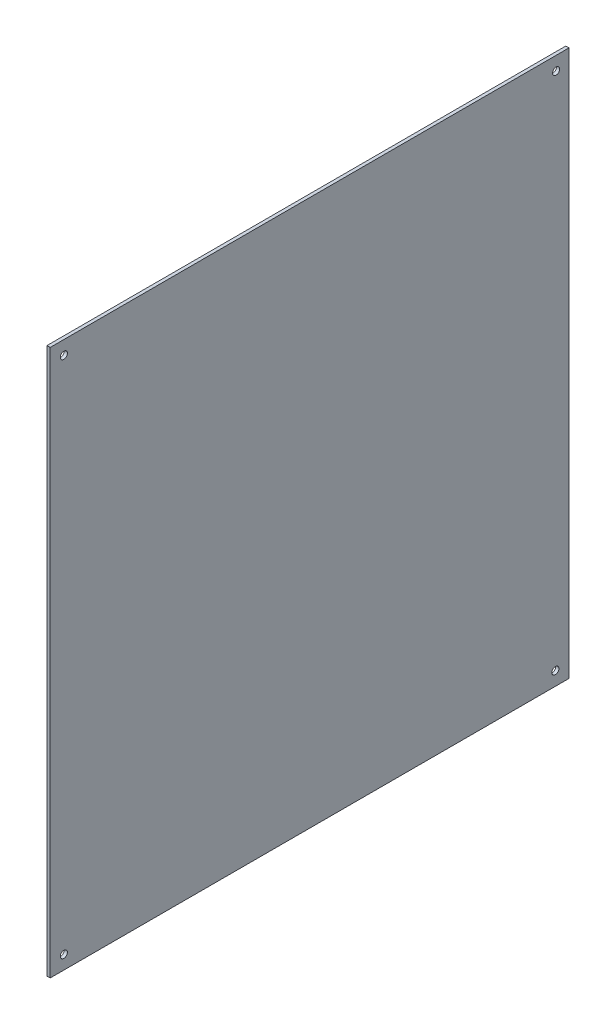
SolidWorks part; units mm, degrees
ref_plane "Front Plane" through (0, 0, 0) normal (0, 0, 1) x (1, 0, 0)
ref_plane "Top Plane" through (0, 0, 0) normal (0, 1, 0) x (1, 0, 0)
ref_plane "Right Plane" through (0, 0, 0) normal (1, 0, 0) x (0, 0, -1)
sketch "Sketch1" plane through (0, 0, 0) normal (1, 0, 0) x (0, 0, -1)
  line L1 (521.5242, 0) -> (1004.1242, 0)
  line L2 (521.5242, 0) -> (521.5242, -508)
  line L3 (521.5242, -508) -> (1004.1242, -508)
  line L4 (1004.1242, 0) -> (1004.1242, -508)
  dimension "D1" = 482.6
  dimension "D2" = 508
extrude "Boss-Extrude1" add sketch "Sketch1" along normal blind 3
sketch "Sketch2" plane through (3, 0, 0) normal (1, 0, 0) x (0, 0, -1)
  line L0 (1004.1242, 0) -> (521.5242, 0) construction
  line L1 (1004.1242, -508) -> (1004.1242, 0) construction
  line L2 (521.5242, 0) -> (521.5242, -508) construction
  line L3 (521.5242, -508) -> (1004.1242, -508) construction
  circle A0 centre (992.1242, -12.7) radius 3.295
  circle A1 centre (534.2242, -12.7) radius 3.295
  circle A2 centre (534.2242, -495.3) radius 3.295
  circle A3 centre (991.4242, -495.3) radius 3.295
  dimension "D1" = 6.59
  dimension "D2" = 6.59
  dimension "D3" = 12.7
  dimension "D4" = 12
  dimension "D5" = 12.7
  dimension "D6" = 12.7
  dimension "D7" = 6.59
  dimension "D8" = 12.7
  dimension "D9" = 12.7
  dimension "D10" = 12.7
  dimension "D11" = 12.7
  dimension "D12" = 6.59
extrude "Cut-Extrude1" cut sketch "Sketch2" against normal blind 3
